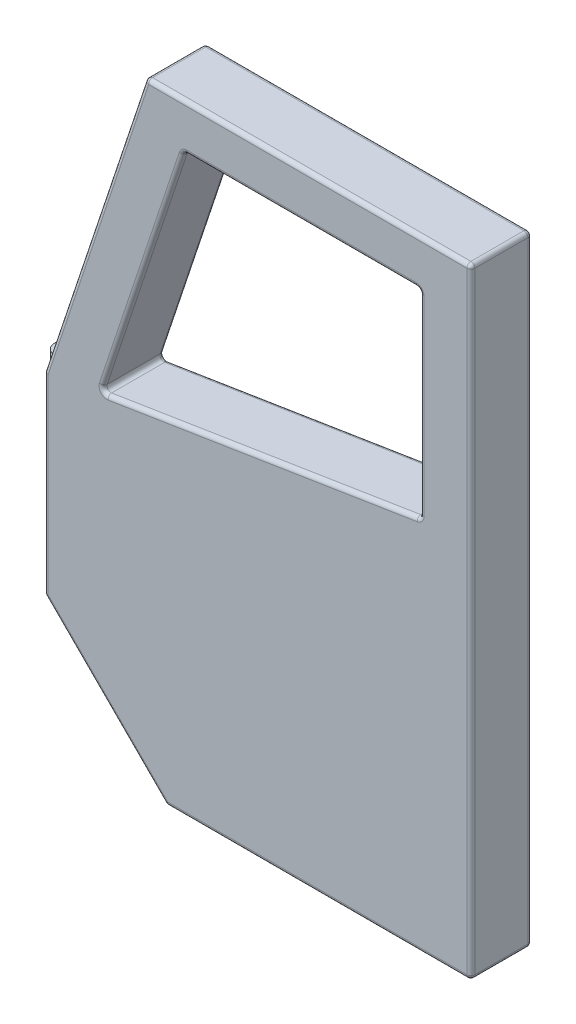
SolidWorks part; units mm, degrees
ref_plane "Front Plane" through (0, 0, 0) normal (0, 0, 1) x (1, 0, 0)
ref_plane "Top Plane" through (0, 0, 0) normal (0, 1, 0) x (1, 0, 0)
ref_plane "Right Plane" through (0, 0, 0) normal (1, 0, 0) x (0, 0, -1)
sketch "Sketch1" plane through (0, 0, 0) normal (0, 0, 1) x (1, 0, 0)
  line L0 (0, 0) -> (-762, 0)
  line L1 (0, 0) -> (0, 1549.4)
  line L2 (0, 1549.4) -> (-812.8, 1549.4)
  line L3 (-812.8, 1549.4) -> (-1066.8, 787.4)
  line L4 (-1066.8, 787.4) -> (-1066.8, 304.8)
  line L5 (-1066.8, 304.8) -> (-762, 0)
  dimension "D1" = 1066.8
  dimension "D2" = 1549.4
  dimension "D3" = 762
  dimension "D4" = 304.8
  dimension "D5" = 304.8
  dimension "D6" = 254
extrude "Boss-Extrude1" add sketch "Sketch1" along normal blind 152.4
sketch "Sketch2" plane through (0, 0, 152.4) normal (0, 0, 1) x (1, 0, 0)
  line L2 (-924.4636, 812.8) -> (-127, 939.8)
  line L3 (-127, 939.8) -> (-127, 1435.1)
  line L4 (-127, 1435.1) -> (-717.0302, 1435.1)
  line L5 (0, 1549.4) -> (-812.8, 1549.4) construction
  line L6 (-924.4636, 812.8) -> (-717.0302, 1435.1)
  line L7 (-812.8, 1549.4) -> (-1066.8, 787.4) construction
  line L8 (0, 0) -> (0, 1549.4) construction
  dimension "D1" = 114.3
  dimension "D2" = 622.3
  dimension "D3" = 127
  dimension "D4" = 127
  dimension "D5" = 127
extrude "Cut-Extrude1" cut sketch "Sketch2" against normal through all
fillet "Fillet1" radius 10 30 edges at (-127, 1435.1, 76.2) (-717.0302, 1435.1, 76.2) (-924.4636, 812.8, 76.2) (-127, 939.8, 76.2) (-127, 1187.45, 0) (-525.7318, 876.3, 0) (-820.7469, 1123.95, 0) (-422.0151, 1435.1, 0) (0, 774.7, 0) (0, 0, 76.2) (-381, 0, 0) (-762, 0, 76.2) (-914.4, 152.4, 0) (0, 1549.4, 76.2) (-406.4, 1549.4, 0) (-812.8, 1549.4, 76.2) (-939.8, 1168.4, 0) (-1066.8, 787.4, 76.2) (-1066.8, 304.8, 76.2) (-1066.8, 546.1, 0) (-381, 0, 152.4) (-914.4, 152.4, 152.4) (-1066.8, 546.1, 152.4) (-939.8, 1168.4, 152.4) (-406.4, 1549.4, 152.4) (0, 774.7, 152.4) (-525.7318, 876.3, 152.4) (-127, 1187.45, 152.4) (-422.0151, 1435.1, 152.4) (-820.7469, 1123.95, 152.4)
ref_plane "Hinge Plane" through (0, 308.9421, 0) normal (0, -1, 0) x (-1, 0, 0)
sketch "Sketch3" plane through (0, 308.9421, 0) normal (0, -1, 0) x (-1, 0, 0)
  line L0 (1066.2868, -76.2) -> (1066.2868, -50.8)
  line L1 (1066.2868, -10) -> (1066.2868, -142.4) construction
  line L3 (1066.2868, -76.2) -> (1066.2868, -101.6)
  line L6 (1066.2868, -50.8) -> (1091.6868, -50.8)
  line L7 (1066.2868, -101.6) -> (1091.6868, -101.6)
  arc A0 (1091.6868, -50.8) -> (1091.6868, -101.6) centre (1091.6868, -76.2) cw
  dimension "D2" = 25.4
  dimension "D1" = 25.4
extrude "Boss-Extrude2" add sketch "Sketch3" against normal up to vertex (476.8351 mm away)
sketch "Sketch4" plane through (-1066.8, 0, 0) normal (-1, 0, 0) x (0, 0, 1)
  line L0 (50.8, 785.7772) -> (50.8, 308.9421) construction
  line L1 (50.8, 658.7772) -> (101.6, 658.7772)
  line L2 (50.8, 658.7772) -> (50.8, 435.9421)
  line L3 (50.8, 435.9421) -> (101.6, 435.9421)
  line L4 (101.6, 658.7772) -> (101.6, 435.9421)
  line L5 (101.6, 785.7772) -> (101.6, 308.9421) construction
  line L6 (-72.82, 308.9421) -> (72.82, 308.9421) construction
  line L7 (101.6, 785.7772) -> (50.8, 785.7772) construction
  dimension "D1" = 127
  dimension "D2" = 127
extrude "Cut-Extrude2" cut sketch "Sketch4" along normal up to surface (24.8868 mm away)
sketch "Sketch6" plane through (0, 308.9421, 0) normal (0, -1, 0) x (-1, 0, 0)
  circle A0 centre (1091.6868, -76.2) radius 15.875
  dimension "D1" = 31.75
extrude "Cut-Extrude3" cut sketch "Sketch6" against normal through all
sketch "Sketch7" plane through (0, 0, 0) normal (0, 0, -1) x (-1, 0, 0)
  line L0 (1056.8, 308.9421) -> (1056.8, 785.7772) construction
  line L1 (1056.8, 598.7772) -> (1016.8, 598.7772)
  line L2 (1056.8, 598.7772) -> (1056.8, 495.9421)
  line L3 (1056.8, 495.9421) -> (1016.8, 495.9421)
  line L4 (1016.8, 598.7772) -> (1016.8, 495.9421)
  line L5 (1091.6868, 658.7772) -> (1066.8, 658.7772) construction
  line L6 (1091.6868, 435.9421) -> (1066.8, 435.9421) construction
  line L7 (1036.8, 598.7772) -> (1036.8, 495.9421) construction
  line L8 (1016.8, 547.3597) -> (1056.8, 547.3597) construction
  circle A0 centre (1036.8, 573.3597) radius 5
  circle A1 centre (1036.8, 521.3597) radius 5
  dimension "D4" = 26
  dimension "D5" = 26
  dimension "D6" = 10
  dimension "D1" = 60
  dimension "D2" = 60
  dimension "D3" = 40
extrude "Boss-Extrude3" add sketch "Sketch7" along normal blind 25.4
